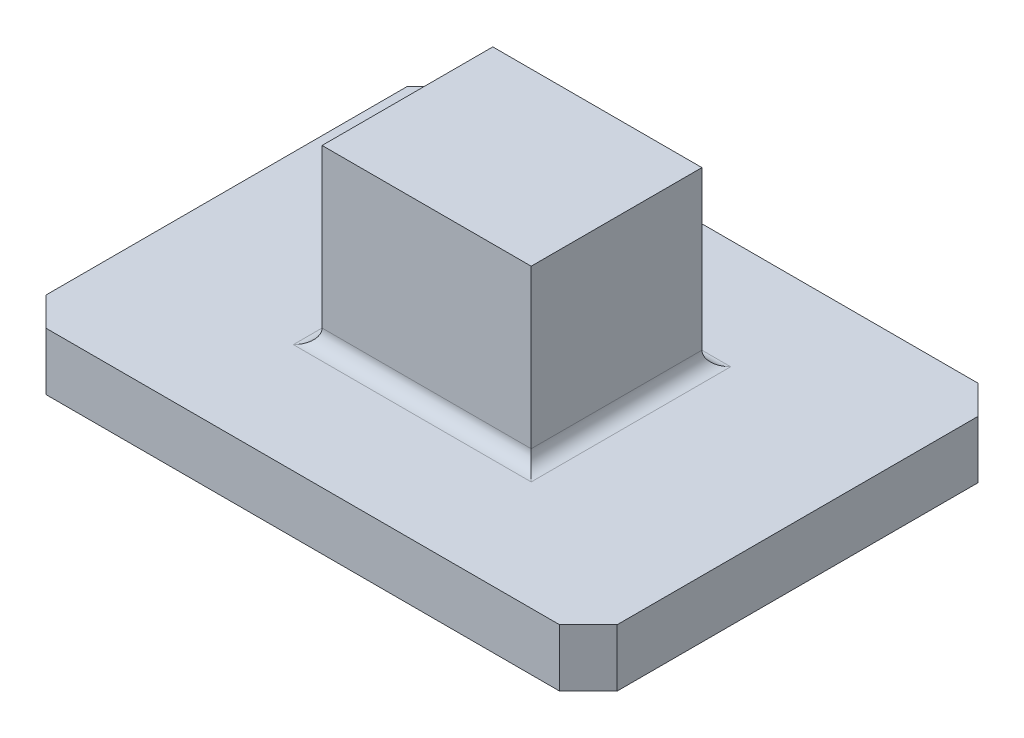
SolidWorks part; units mm, degrees
ref_plane "Plan de face" through (0, 0, 0) normal (0, 0, 1) x (1, 0, 0)
ref_plane "Plan de dessus" through (0, 0, 0) normal (0, 1, 0) x (1, 0, 0)
ref_plane "Plan de droite" through (0, 0, 0) normal (1, 0, 0) x (0, 0, -1)
sketch "Esquisse1" plane through (0, 0, 0) normal (0, 1, 0) x (1, 0, 0)
  line L1 (-99.3307, -72.7706) -> (99.3307, -72.7706)
  line L2 (-99.3307, -72.7706) -> (-99.3307, 72.7706)
  line L3 (-99.3307, 72.7706) -> (99.3307, 72.7706)
  line L4 (99.3307, -72.7706) -> (99.3307, 72.7706)
  line L5 (-99.3307, -72.7706) -> (99.3307, 72.7706) construction
  line L6 (-99.3307, 72.7706) -> (99.3307, -72.7706) construction
  point P1 (0, 0)
extrude "Boss.-Extru.1" add sketch "Esquisse1" along normal blind 20
sketch "Esquisse2" plane through (0, 20, 0) normal (0, 1, 0) x (1, 0, 0)
  line L1 (-36.3701, -29.6961) -> (36.3701, -29.6961)
  line L2 (-36.3701, -29.6961) -> (-36.3701, 29.6961)
  line L3 (-36.3701, 29.6961) -> (36.3701, 29.6961)
  line L4 (36.3701, -29.6961) -> (36.3701, 29.6961)
  line L5 (-36.3701, -29.6961) -> (36.3701, 29.6961) construction
  line L6 (-36.3701, 29.6961) -> (36.3701, -29.6961) construction
  point P0 (0, 0)
extrude "Boss.-Extru.2" add sketch "Esquisse2" along normal blind 60
fillet "Congé1" radius 5 4 edges at (0, 20, -29.6961) (-36.3701, 20, 0) (36.3701, 20, 0) (0, 20, 29.6961)
chamfer "Chanfrein1" distance 10 angle 45 4 edges at (-99.3307, 10, -72.7706) (99.3307, 10, -72.7706) (-99.3307, 10, 72.7706) (99.3307, 10, 72.7706)
